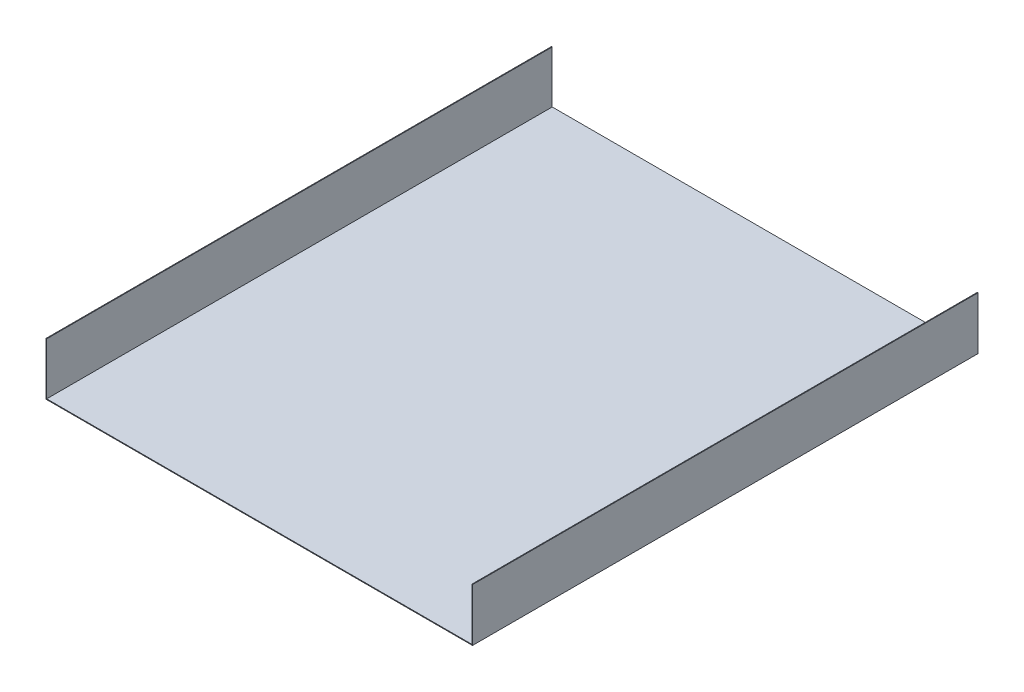
SolidWorks part; units mm, degrees
ref_plane "Front Plane" through (0, 0, 0) normal (0, 0, 1) x (1, 0, 0)
ref_plane "Top Plane" through (0, 0, 0) normal (0, 1, 0) x (1, 0, 0)
ref_plane "Right Plane" through (0, 0, 0) normal (1, 0, 0) x (0, 0, -1)
other "Configuration Table"
sketch "Sketch1" plane through (0, 0, 0) normal (0, 0, 1) x (1, 0, 0)
  line L0 (13.7, 81) -> (13.7, 8)
  line L1 (13.7, 8) -> (604.3, 8)
  line L2 (604.3, 8) -> (604.3, 81)
  line L3 (604.3, 81) -> (603.3, 81)
  line L4 (603.3, 81) -> (603.3, 9)
  line L5 (603.3, 9) -> (14.7, 9)
  line L6 (14.7, 9) -> (14.7, 81)
  line L7 (14.7, 81) -> (13.7, 81)
extrude "CEK_taze_kutu_U_1.0_1" add sketch "Sketch1" against normal blind 700 separate body
